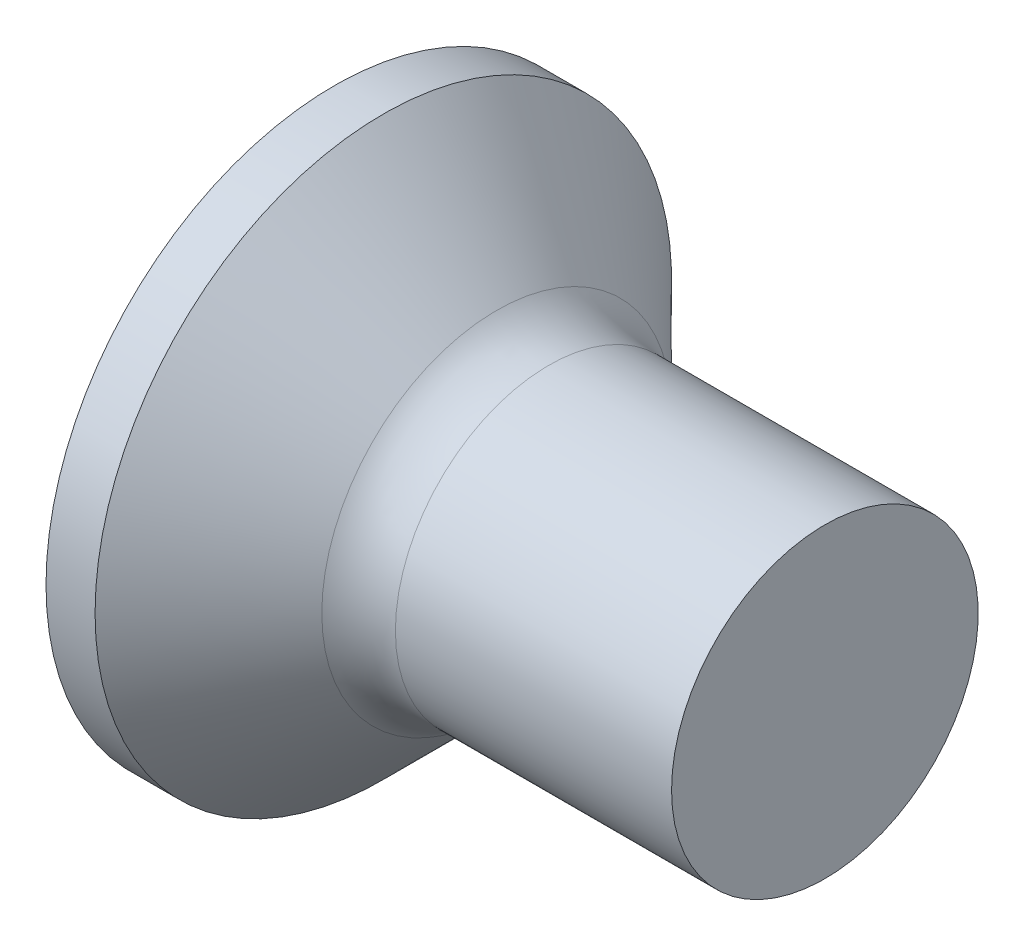
SolidWorks part; units mm, degrees
revolve "Base-Revolve" add sketch "BodySke"
sketch "BodySke" plane through (0, 0, 0) normal (0, 0, 1) x (1, 0, 0)
  line L0 (0, 0) -> (0, 2.35)
  line L1 (0, 2.35) -> (0.4, 2.35)
  line L2 (1.5, 1.25) -> (4, 1.25)
  line L3 (4, 1.25) -> (4, 0)
  line L4 (4, 0) -> (0, 0)
  line L5 (-6.35, 0) -> (82.55, 0) construction
  line L6 (1.5, -1.25) -> (4, -1.25) construction
  line L7 (0.4, -2.35) -> (1.5, -1.25) construction
  line L8 (0.4, 2.35) -> (1.5, 1.25)
  line L9 (0, -2.35) -> (0.4, -2.35) construction
  line L10 (1.95, 2.8375) -> (1.95, -6.6875) construction
  line L11 (-2, 6.35) -> (-2, -3.175) construction
  dimension "Diameter" = 2.5
  dimension "Length" = 4
  dimension "Head_ht" = 1.5
  dimension "Head_dia" = 4.7
  dimension "Head_ang" = 90
  dimension "D6" = 0.4
  dimension "Advance" = 0.45
  dimension "Thread_nom" = 6
cosmetic thread "ThreadCosmetic" [suppressed]
fillet "Fillet1" radius 0.6 1 edges at (1.5, 0, 1.25)
material "Plastique personnalisé"
ref_plane "Plane1" through (0, 0, 0) normal (0, 0, 1) x (1, 0, 0)
ref_plane "Plane2" through (0, 0, 0) normal (0, 1, 0) x (1, 0, 0)
ref_plane "Plane3" through (0, 0, 0) normal (1, 0, 0) x (0, 0, -1)
sketch "Sketch3" plane through (0, 0, 0) normal (-1, 0, 0) x (0, 0, 1)
  line L0 (-0.37, 1.4) -> (0.37, 1.4)
  line L1 (0.37, 1.4) -> (0.37, -1.4)
  line L2 (0.37, -1.4) -> (-0.37, -1.4)
  line L3 (-0.37, -1.4) -> (-0.37, 1.4)
  dimension "Cross_dia" = 2.8
  dimension "Cross_width" = 0.74
  dimension "D1" = 1.4
  dimension "D2" = 0.37
ref_plane "Plane4" through (1.73, 0, 0) normal (-1, 0, 0) x (0, 0, 1)
sketch "Sketch4" plane through (1.73, 0, 0) normal (-1, 0, 0) x (0, 0, 1)
  line L0 (-0.37, 0.5375) -> (0.37, 0.5375)
  line L3 (0.37, 0.5375) -> (0.37, -0.5375)
  line L4 (0.37, -0.5375) -> (-0.37, -0.5375)
  line L5 (-0.37, -0.5375) -> (-0.37, 0.5375)
  dimension "D2" = 1.0749
  dimension "D1" = 0.74
  dimension "D4" = 0.5375
  dimension "D3" = 0.37
loft "Recess" cut profiles "Sketch3", "Sketch4"
pattern_circular "RecPat" count 2 every 90 about axis through (0, 0, 0) along (1, 0, 0) of "Recess"
sketch "RecCorSke" plane through (0, 0, 0) normal (0, 0, 1) x (1, 0, 0)
  line L0 (-3.175, 0) -> (15.875, 0) construction
  line L2 (0, 0) -> (0, 0.677)
  line L3 (0, 0.677) -> (1.73, 0.556)
  line L4 (1.73, 0.556) -> (1.9107, 0)
  line L5 (1.9107, 0) -> (0, 0)
  dimension "Diameter" = 1.112
  dimension "Depth" = 1.73
  dimension "Draft_angle" = 4
  dimension "Bottom_angle" = 18
revolve "RecessCore" cut sketch "RecCorSke" angle 360 about L0
sketch "ThdSchSke" plane through (0, 0, 0) normal (0, 0, 1) x (1, 0, 0)
  line L0 (1.95, -0.9965) -> (1.7725, -1.25)
  line L1 (1.95, -0.9965) -> (2.1275, -1.25)
  line L2 (2.1275, -1.25) -> (2.1275, -1.5625)
  line L3 (-3.175, 0) -> (5.1513, 0) construction
  line L5 (2.1275, -1.5625) -> (1.7725, -1.5625)
  line L6 (1.7725, -1.5625) -> (1.7725, -1.25)
  line L7 (0, 2.35) -> (0, -2.35) construction
  dimension "Diameter" = 2.5
  dimension "Thread_minor" = 1.993
  dimension "Start" = 1.95
revolve "ThreadSchematic" [suppressed] cut sketch "ThdSchSke" angle 360 about L3
pattern_linear "ThdSchPat" [suppressed]
equation "\"D1@Sketch3\" = \"Cross_dia@Sketch3\" / 2"
equation "\"D2@Sketch3\" = \"Cross_width@Sketch3\" / 2"
equation "\"Depth@RecCorSke\" = \"Cross_depth@Plane4\""
equation "\"D1@Sketch4\" = \"Cross_width@Sketch3\""
equation "\"D2@Sketch4\" = \"Cross_dia@Sketch3\" - 2.0 * \"Cross_depth@Plane4\" * tan(26.5  * 0.017453292)"
equation "\"D3@Sketch4\" = \"D1@Sketch4\" / 2"
equation "\"D4@Sketch4\" = \"D2@Sketch4\" / 2"
equation "\"Thread_length@ThreadCosmetic\" = ((sgn( (\"Length@BodySke\" - \"Advance@BodySke\" * 1.0 - \"Head_ht@BodySke\" ) - \"Thread_nom@BodySke\" )-1)*( (\"Length@BodySke\" - \"Advance@BodySke\" * 1.0 - \"Head_ht@BodySke\" ) - \"Thread_nom@BodySke\" ))/-2+ \"Thread_nom@BodySke\""
equation "\"Thread_minor@ThdSchSke\" = \"Thread_minor@ThreadCosmetic\""
equation "\"Diameter@ThdSchSke\" = \"Diameter@BodySke\""
equation "\"Overcut@ThdSchSke\" = \"Diameter@BodySke\" * 1.25"
equation "\"Start@ThdSchSke\" = 0.000001 + \"Length@BodySke\" - \"Thread_length@ThreadCosmetic\"  '---Countersunk---"
equation "\"Num_threads@ThdSchPat\" = int( \"Thread_length@ThreadCosmetic\" / \"Advance@BodySke\" + 0.999 )  + 1"
equation "\"Advance@ThdSchPat\" = \"Thread_length@ThreadCosmetic\" /  (\"Num_threads@ThdSchPat\" - 1) 'relax it"
